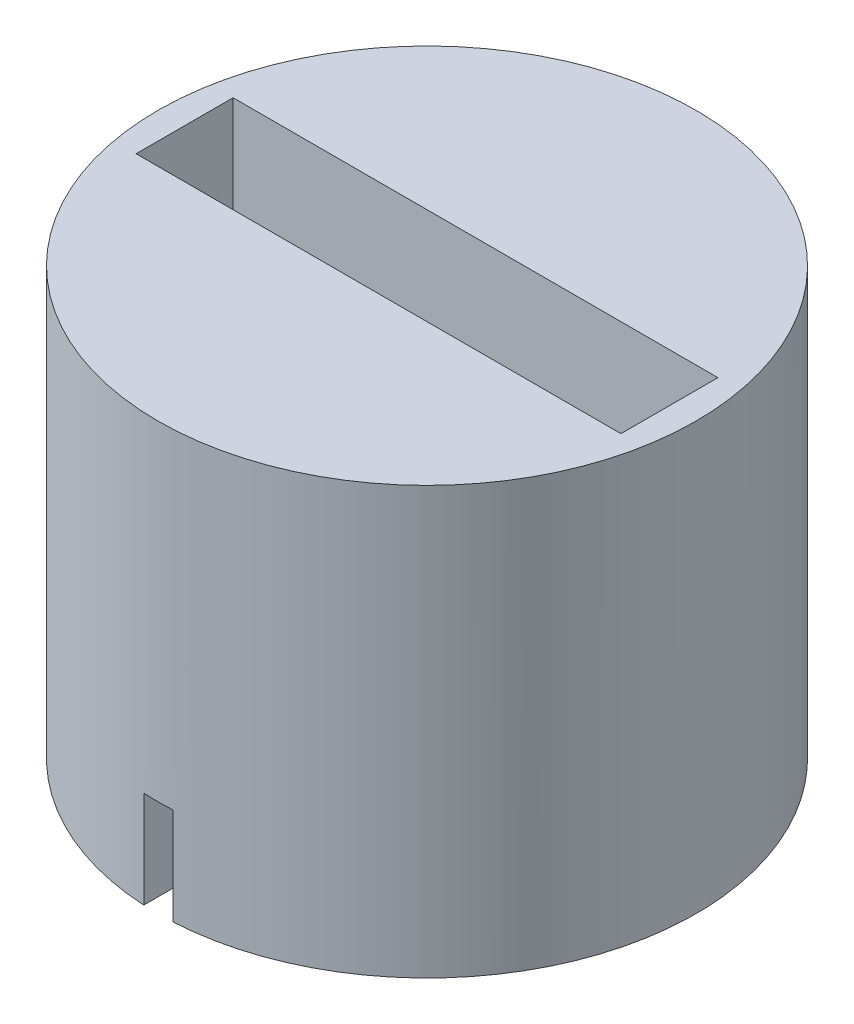
SolidWorks part; units mm, degrees
ref_plane "Front Plane" through (0, 0, 0) normal (0, 0, 1) x (1, 0, 0)
ref_plane "Top Plane" through (0, 0, 0) normal (0, 1, 0) x (1, 0, 0)
ref_plane "Right Plane" through (0, 0, 0) normal (1, 0, 0) x (0, 0, -1)
sketch "Sketch1" plane through (0, 0, 0) normal (0, 1, 0) x (1, 0, 0)
  circle A0 centre (0, 0) radius 13.875
extrude "Boss-Extrude1" add sketch "Sketch1" along normal blind 22
sketch "Sketch2" plane through (0, 0, 0) normal (0, -1, 0) x (1, 0, 0)
  line L1 (-0.75, 14.9247) -> (0.75, 14.9247)
  line L2 (-0.75, 14.9247) -> (-0.75, 12)
  line L3 (-0.75, 12) -> (0.75, 12)
  line L4 (0.75, 14.9247) -> (0.75, 12)
  line L5 (-0.75, -12) -> (0.75, -12)
  line L6 (-0.75, -12) -> (-0.75, -16.4668)
  line L7 (-0.75, -16.4668) -> (0.75, -16.4668)
  line L8 (0.75, -12) -> (0.75, -16.4668)
  dimension "D1" = 1.5
  dimension "D2" = 12
  dimension "D3" = 0.75
  dimension "D4" = 12
extrude "Cut-Extrude1" cut sketch "Sketch2" against normal blind 5
sketch "Sketch3" plane through (0, 22, 0) normal (0, 1, 0) x (1, 0, 0)
  line L1 (12.5, 2.5) -> (12.5, -2.5)
  line L2 (12.5, 2.5) -> (-12.5, 2.5)
  line L3 (-12.5, 2.5) -> (-12.5, -2.5)
  line L4 (12.5, -2.5) -> (-12.5, -2.5)
  dimension "D1" = 25
  dimension "D2" = 5
  dimension "D3" = 2.5
  dimension "D4" = 12.5
extrude "Cut-Extrude2" cut sketch "Sketch3" against normal blind 20
